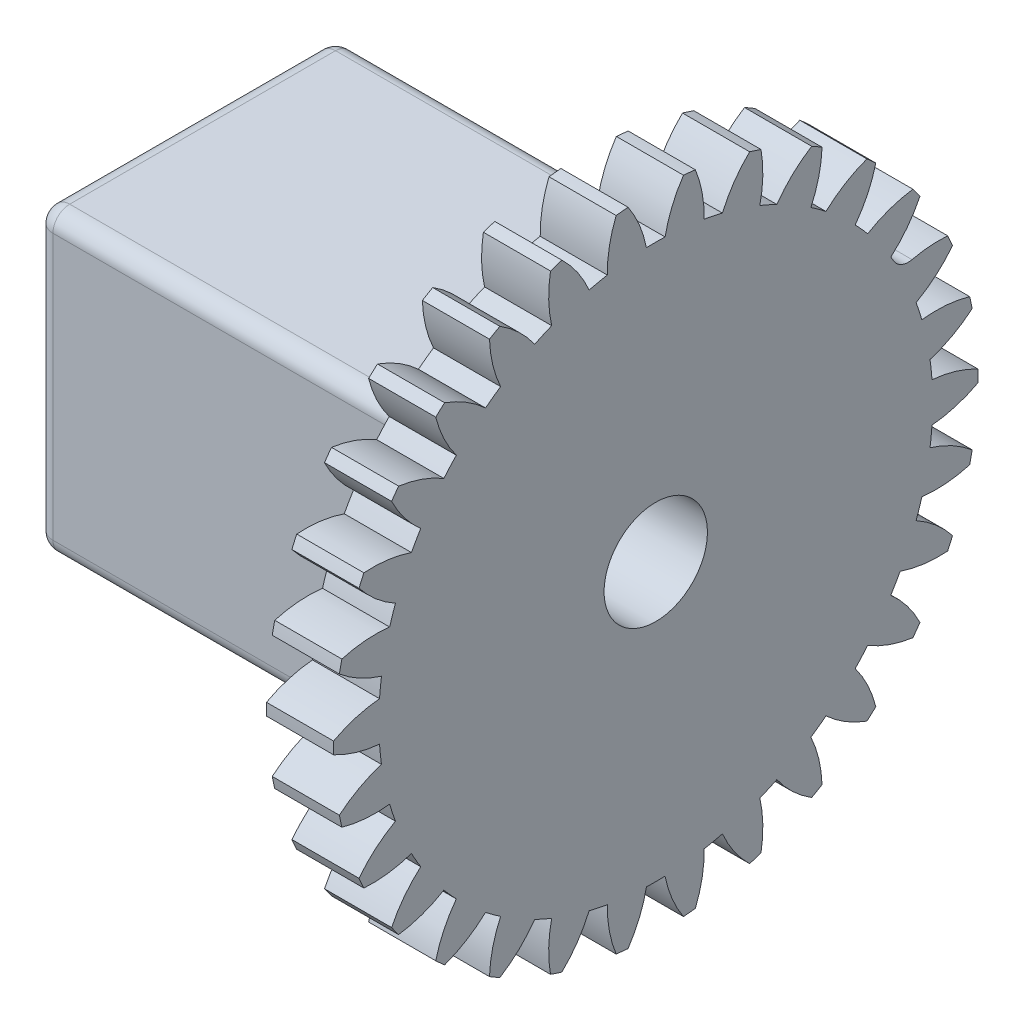
SolidWorks part; units mm, degrees
material "Custom Plastic"
ref_plane "Plane1" through (0, 0, 0) normal (0, 0, 1) x (1, 0, 0)
ref_plane "Plane2" through (0, 0, 0) normal (0, 1, 0) x (1, 0, 0)
ref_plane "Plane3" through (0, 0, 0) normal (1, 0, 0) x (0, 0, -1)
other "Configuration Table"
sketch "HoldingSke" plane through (0, 0, 0) normal (0, 1, 0) x (1, 0, 0)
  line L0 (0, 0) -> (0.2887, -0.1667)
  line L1 (-15, 0) -> (100, 0) construction
  line L2 (0, 0) -> (-2.1039, 2.3779)
  line L3 (0, 0) -> (-11.863, 4.5341)
  line L4 (0, 0) -> (7.479, 4.318)
  line L5 (0, 0) -> (-46.8476, -17.4728)
  line L6 (0, 0) -> (-8.2896, -5.593)
  line L7 (-2.1039, 2.3779) -> (8.6586, 51.2059)
  line L8 (-76.2, 54.61) -> (-74.4, 54.61)
  line L9 (-71.009, 38.7566) -> (-53.1078, 45.2721)
  line L10 (-76.2, 71.12) -> (104.1128, 71.12)
  line L11 (0, 0) -> (-10, 0)
  line L12 (-76.2, 101.6) -> (-76.093, 101.6)
  line L13 (24.9733, 27.94) -> (52.9518, 28.4284)
  line L14 (24.9733, 27.94) -> (24.9743, 27.94)
  line L15 (24.9733, 27.94) -> (100.4006, 29.5858)
  line L16 (-63.627, -3) -> (-12.827, -3)
  circle A0 centre (0, 0) radius 5
  circle A1 centre (0, 0) radius 37.5
  circle A2 centre (0, 0) radius 37.5
  circle A3 centre (0, 0) radius 5
  dimension "MHD" = 75
  dimension "Hub_dia" = 75
  dimension "Bore" = 10
  dimension "MBD" = 10
  dimension "Num_teeth" = 30
  dimension "Pitch" = 0.3333
  dimension "Overall_len" = 50
  dimension "Show_teeth" = 30
  dimension "Thickness" = 10
  dimension "OAL" = 50.0001
  dimension "T_dim" = 1.8
  dimension "Ap" = 20
  dimension "H" = 19.05
  dimension "Pitch_radius" = 180.3128
  dimension "Width" = 10
  dimension "Backlash" = 0.107
  dimension "Addendum_fac" = 1
  dimension "Dedendum_fac" = 1.25
  dimension "Clearance_fac" = 0.25
  dimension "Dedendum_add" = 0.001
  dimension "Module" = 3
sketch "BasProSke" plane through (0, 0, 0) normal (0, 1, 0) x (1, 0, 0)
  line L0 (-10, 0) -> (60, 0) construction
  line L1 (0, 0) -> (0, 48)
  line L2 (0, 0) -> (10, 0)
  line L3 (10, 0) -> (10, 48)
  line L4 (10, 48) -> (0, 48)
  dimension "Thickness" = 10
  dimension "Diameter" = 96
revolve "Base-Revolve" add sketch "BasProSke" angle 360 about L0
sketch "TooCutSke" plane through (0, 0, 0) normal (1, 0, 0) x (0, 0, -1)
  line L1 (0, 0) -> (0, 107) construction
  line L2 (0, 0) -> (-2.5423, 44.9281) construction
  line L3 (0, 0) -> (-9.3966, 89.403) construction
  line L4 (-2.5423, 44.9281) -> (-4.6983, 44.7015) construction
  arc A0 (1.3884, 41.2256) -> (-1.3884, 41.2256) centre (0, 0) ccw
  arc A1 (4.1466, 47.8461) -> (-4.1466, 47.8461) centre (0, 0) ccw
  circle A2 centre (0, 0) radius 45 construction
  circle A3 centre (0, 0) radius 42.2862 construction
  arc A4 (-1.3884, 41.2256) -> (-4.1466, 47.8461) centre (-19.05, 37.752) ccw
  arc A5 (4.1466, 47.8461) -> (1.3884, 41.2256) centre (19.05, 37.752) ccw
  dimension "Root_dia" = 82.498
  dimension "Overcut_dia" = 96.0508
  dimension "Pitch_dia" = 90
  dimension "Base_dia" = 84.5723
  dimension "Flank_rad" = 18
  dimension "Half_ang" = 6
  dimension "Half_CT" = 2.1679
extrude "ToothCut" cut sketch "TooCutSke" along normal through all
fillet "Breaks" [suppressed] radius 0.06
fillet "RootFillets" [suppressed] radius 0.751
pattern_circular "TeethCuts" count 30 every 12 about axis through (-10, 0, 0) along (1, 0, 0) of "ToothCut", "RootFillets", "Breaks"
sketch "HubNeaOneSke" plane through (0, 0, 0) normal (-1, 0, 0) x (0, 0, 1)
  circle A0 centre (0, 0) radius 37.5
  dimension "Diameter" = 75
extrude "HubNearOne" [suppressed] add sketch "HubNeaOneSke" along normal blind 40.0001
sketch "HubNeaBotSke" plane through (0, 0, 0) normal (-1, 0, 0) x (0, 0, 1)
  circle A0 centre (0, 0) radius 37.5
  dimension "Diameter" = 75
extrude "HubNearBoth" [suppressed] add sketch "HubNeaBotSke" along normal blind 20
ref_plane "FarPln" through (10, 0, 0) normal (1, 0, 0) x (0, 0, -1)
sketch "HubFarSke" plane through (10, 0, 0) normal (1, 0, 0) x (0, 0, -1)
  circle A0 centre (0, 0) radius 37.5
  dimension "Diameter" = 75
extrude "HubFar" [suppressed] add sketch "HubFarSke" along normal blind 20
sketch "BorSke" plane through (0, 0, 0) normal (1, 0, 0) x (0, 0, -1)
  circle A0 centre (0, 0) radius 5
  dimension "Diameter" = 10
extrude "Bore" cut sketch "BorSke" along normal mid plane 100.0001
sketch "KeySke" plane through (0, 0, 0) normal (1, 0, 0) x (0, 0, -1)
  line L0 (-2, 0) -> (-2, 6.8)
  line L1 (-2, 6.8) -> (2, 6.8)
  line L2 (2, 6.8) -> (2, 0)
  line L3 (0, 0) -> (0, 34) construction
  line L4 (-2, 0) -> (2, 0)
  dimension "Offset" = 6.8
  dimension "Width" = 4
extrude "Keyway" [suppressed] cut sketch "KeySke" along normal mid plane 100.0001
pattern_circular "Keyway2" [suppressed] count 2 every 90 about axis through (-10, 0, 0) along (1, 0, 0)
sketch "Sketch1" plane through (10, 0, 0) normal (1, 0, 0) x (0, 0, -1)
  circle A0 centre (0, 0) radius 7.7
  dimension "D1" = 15.4
sketch "Sketch2" plane through (0, 0, 0) normal (-1, 0, 0) x (0, 0, 1)
  line L0 (-22.3, 22.3) -> (22.3, -22.3) construction
  line L1 (-22.3, 22.3) -> (22.3, 22.3)
  line L2 (-22.3, 22.3) -> (-22.3, -22.3)
  line L3 (-22.3, -22.3) -> (22.3, -22.3)
  line L4 (22.3, 22.3) -> (22.3, -22.3)
  dimension "D1" = 44.6
extrude "Boss-Extrude1" add sketch "Sketch2" along normal blind 60
extrude "Cut-Extrude1" cut sketch "Sketch1" against normal up to next
fillet "Fillet2" radius 2.5 14 edges at (0, 22.3, 0) (-30, 22.3, 22.3) (-30, -22.3, 22.3) (0, -22.3, 0) (-60, 22.3, 0) (-60, 0, 22.3) (-60, 0, 7.7) (-30, 22.3, -22.3) (-60, 0, -22.3) (0, 0, -22.3) (5, 19.4105, -36.3966) (0, 0, 22.3) (-30, -22.3, -22.3) (-60, -22.3, 0)
equation "' \"Module@HoldingSke\" = 6.35"
equation "' \"Num_teeth@HoldingSke\" = 12"
equation "' \"Ap@HoldingSke\" =  20"
equation "' \"Ap@HoldingSke\" = 20"
equation "' \"Width@HoldingSke\" = 0.5 * 25.4"
equation "' \"Hub_dia@HoldingSke\"= 1 * 25.4"
equation "' \"Hub_dia@HoldingSke\" = 1 * 25.4"
equation "' \"Overall_len@HoldingSke\" = 1.0 * 25.4"
equation "' \"Bore@HoldingSke\" = 0.75 * 25.4"
equation "' \"T_dim@HoldingSke\" = 0.1 * 25.4"
equation "' \"Width@KeySke\" = 0.25 * 25.4"
equation "' \"Show_teeth@HoldingSke\" = 13"
equation "' \"Backlash@HoldingSke\" = 0.009 * 25.4"
equation "' \"Addendum_fac@HoldingSke\" = 1.0"
equation "' \"Dedendum_fac@HoldingSke\" = 1.25"
equation "' \"Dedendum_add@HoldingSke\" = 0.00005 * 25.4"
equation "' \"Clearance_fac@HoldingSke\" = 0.25"
equation "\"Pitch@HoldingSke\" = 1 / \"Module@HoldingSke\""
equation "\"Overcut_dia@TooCutSke\" = (\"Num_teeth@HoldingSke\" + 2 * \"Addendum_fac@HoldingSke\") / \"Pitch@HoldingSke\" + 0.002 * 25.4"
equation "\"Pitch_dia@TooCutSke\" = \"Num_teeth@HoldingSke\" / \"Pitch@HoldingSke\""
equation "\"Base_dia@TooCutSke\" = \"Num_teeth@HoldingSke\" / \"Pitch@HoldingSke\" * cos((\"Ap@HoldingSke\"  * 3.14159265 / 180))"
equation "\"Root_dia@TooCutSke\" = (\"Num_teeth@HoldingSke\" + 2) / \"Pitch@HoldingSke\" - 2 * (\"Addendum_fac@HoldingSke\" + \"Dedendum_fac@HoldingSke\") / \"Pitch@HoldingSke\" - \"Dedendum_add@HoldingSke\" * 2"
equation "\"Half_ang@TooCutSke\" = 180 / \"Num_teeth@HoldingSke\""
equation "\"Half_CT@TooCutSke\" = \"Num_teeth@HoldingSke\" / \"Pitch@HoldingSke\" * sin((3.14159265 / 2 / \"Num_teeth@HoldingSke\")) / 2 - 7 * \"Backlash@HoldingSke\" / 4"
equation "\"Flank_rad@TooCutSke\" = \"Num_teeth@HoldingSke\" / \"Pitch@HoldingSke\" / 5"
equation "\"Radius@RootFillets\" = \"Clearance_fac@HoldingSke\" / \"Pitch@HoldingSke\" + \"Dedendum_add@HoldingSke\""
equation "\"Break_rad@Breaks\" = 0.02 / \"Pitch@HoldingSke\""
equation "\"Thickness@HoldingSke\" = \"Width@HoldingSke\""
equation "\"OAL@HoldingSke\" = \"Thickness@HoldingSke\""
equation "\"MHD@HoldingSke\" = (\"Num_teeth@HoldingSke\" + 2) / \"Pitch@HoldingSke\" - 2 * (\"Addendum_fac@HoldingSke\" + \"Dedendum_fac@HoldingSke\")  / \"Pitch@HoldingSke\" - \"Dedendum_add@HoldingSke\" * 2"
equation "\"MBD@HoldingSke\" = (\"Num_teeth@HoldingSke\" + 2) / \"Pitch@HoldingSke\" - 2 * (\"Addendum_fac@HoldingSke\" + \"Dedendum_fac@HoldingSke\")  / \"Pitch@HoldingSke\" - \"Dedendum_add@HoldingSke\" * 2 - 0.002 * 25.4"
equation "\"MHD@HoldingSke\" = ((sgn( \"MHD@HoldingSke\" - \"Hub_dia@HoldingSke\" )-1)*( \"MHD@HoldingSke\" - \"Hub_dia@HoldingSke\" ))/-2+ \"Hub_dia@HoldingSke\""
equation "\"MBD@HoldingSke\" = ((sgn( \"MBD@HoldingSke\" - \"Bore@HoldingSke\" )-1)*( \"MBD@HoldingSke\" - \"Bore@HoldingSke\" ))/-2+ \"Bore@HoldingSke\""
equation "\"OAL@HoldingSke\" = ((sgn( \"OAL@HoldingSke\" - \"Overall_len@HoldingSke\" )+1)*( \"OAL@HoldingSke\" - \"Overall_len@HoldingSke\" ))/2 + \"Overall_len@HoldingSke\" + 0.000002 * 25.4"
equation "\"Num_teeth@TeethCuts\" = int( \"Show_teeth@HoldingSke\" ) + 1"
equation "\"Num_teeth@TeethCuts\" = ((sgn( \"Num_teeth@TeethCuts\" - \"Num_teeth@HoldingSke\" )-1)*( \"Num_teeth@TeethCuts\" - \"Num_teeth@HoldingSke\" ))/-2+ \"Num_teeth@HoldingSke\""
equation "\"Num_teeth@TeethCuts\" = ((sgn( \"Num_teeth@TeethCuts\" - 2.0)+1)*( \"Num_teeth@TeethCuts\" - 2.0))/2 +2.0"
equation "\"Angle@TeethCuts\" = 360.0 / \"Num_teeth@HoldingSke\""
equation "\"Diameter@BasProSke\" = (\"Num_teeth@HoldingSke\" + 2 * \"Addendum_fac@HoldingSke\") / \"Pitch@HoldingSke\""
equation "\"Thickness@BasProSke\"  = \"Thickness@HoldingSke\""
equation "' \"Fillet_rad@BasProSke\" =  \"Thickness@HoldingSke\" * 0.05"
equation "' \"Fillet_rad@BasProSke\" = \"Thickness@HoldingSke\" * 0.05"
equation "\"MHD@HoldingSke\" = ((sgn( \"MHD@HoldingSke\" - \"Root_dia@TooCutSke\" )-1)*( \"MHD@HoldingSke\" - \"Root_dia@TooCutSke\" ))/-2+ \"Root_dia@TooCutSke\""
equation "\"Diameter@HubNeaOneSke\" = \"MHD@HoldingSke\""
equation "\"Length@HubNearOne\" = \"OAL@HoldingSke\" - \"Thickness@BasProSke\""
equation "\"Diameter@HubNeaBotSke\" = \"MHD@HoldingSke\""
equation "\"Length@HubNearBoth\" = ( \"OAL@HoldingSke\" - \"Thickness@BasProSke\" ) / 2.0"
equation "\"Thickness@FarPln\" = \"Thickness@BasProSke\""
equation "\"Diameter@HubFarSke\" = \"MHD@HoldingSke\""
equation "\"Length@HubFar\" = ( \"OAL@HoldingSke\" - \"Thickness@BasProSke\" ) / 2.0"
equation "\"Diameter@BorSke\" = \"MBD@HoldingSke\""
equation "\"D1@Bore\" = \"OAL@HoldingSke\" * 2.0"
equation "\"D1@Keyway\" = \"OAL@HoldingSke\" * 2.0"
equation "\"Offset@KeySke\" = \"T_dim@HoldingSke\" + \"MBD@HoldingSke\" / 2.0"
